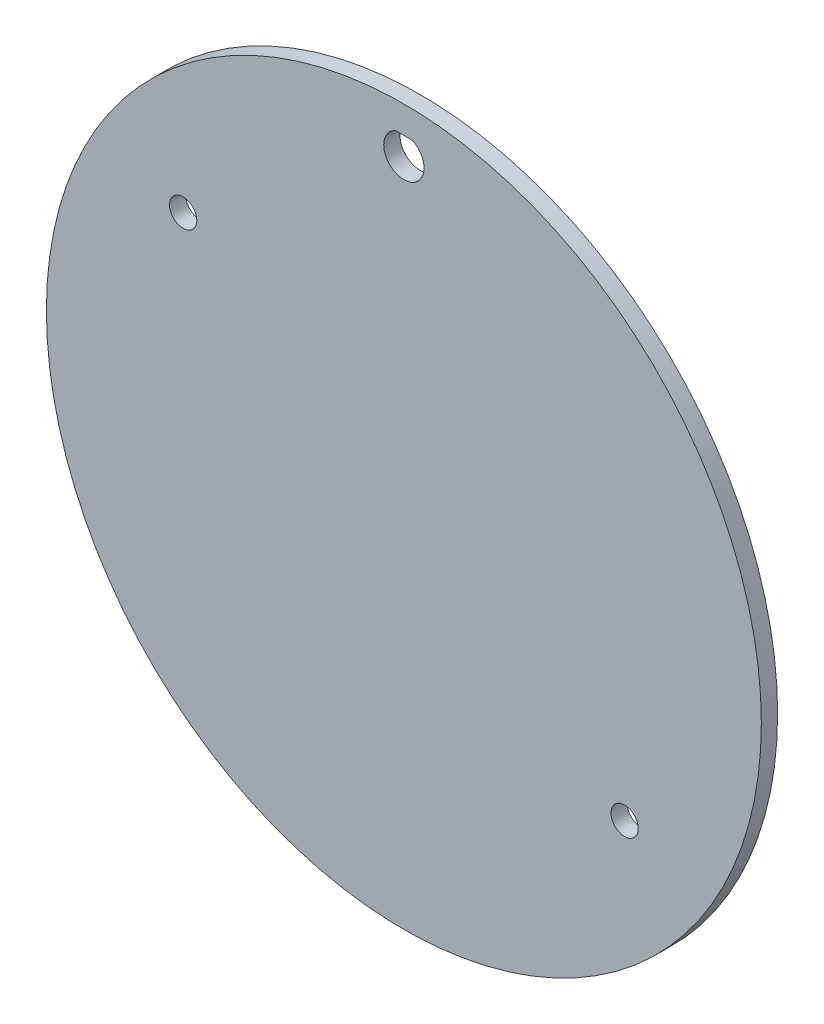
SolidWorks part; units mm, degrees
material "1100-H12 Barre (SS)"
ref_plane "Plan de face" through (0, 0, 0) normal (0, 0, 1) x (1, 0, 0)
ref_plane "Plan de dessus" through (0, 0, 0) normal (0, 1, 0) x (1, 0, 0)
ref_plane "Plan de droite" through (0, 0, 0) normal (1, 0, 0) x (0, 0, -1)
sketch "Esquisse1" plane through (0, 0, 0) normal (0, 0, 1) x (1, 0, 0)
  circle A0 centre (0, 0) radius 55
  dimension "D1" = 110
extrude "Boss.-Extru.1" add sketch "Esquisse1" along normal blind 2.5
sketch "Esquisse2" plane through (0, 0, 2.5) normal (0, 0, 1) x (1, 0, 0)
  circle A0 centre (33.9599, -23.5374) radius 2.1
  circle A1 centre (-33.9599, 23.5374) radius 2.1
  dimension "D1" = 4.2
  dimension "D2" = 4.2
extrude "Enlèv. mat.-Extru.1" cut sketch "Esquisse2" against normal through all
sketch "Esquisse3" plane through (0, 0, 2.5) normal (0, 0, 1) x (1, 0, 0)
  line L0 (0, 48) -> (0, 0) construction
  line L1 (1.3304, 50.8) -> (-1.3304, 50.8)
  arc A1 (-1.3304, 50.8) -> (1.3304, 50.8) centre (0, 48) ccw
  point P5 (0, 44.9)
  dimension "D1" = 3.1
  dimension "D2" = 48
  dimension "D3" = 5.9
extrude "Enlèv. mat.-Extru.2" cut sketch "Esquisse3" against normal blind 10
